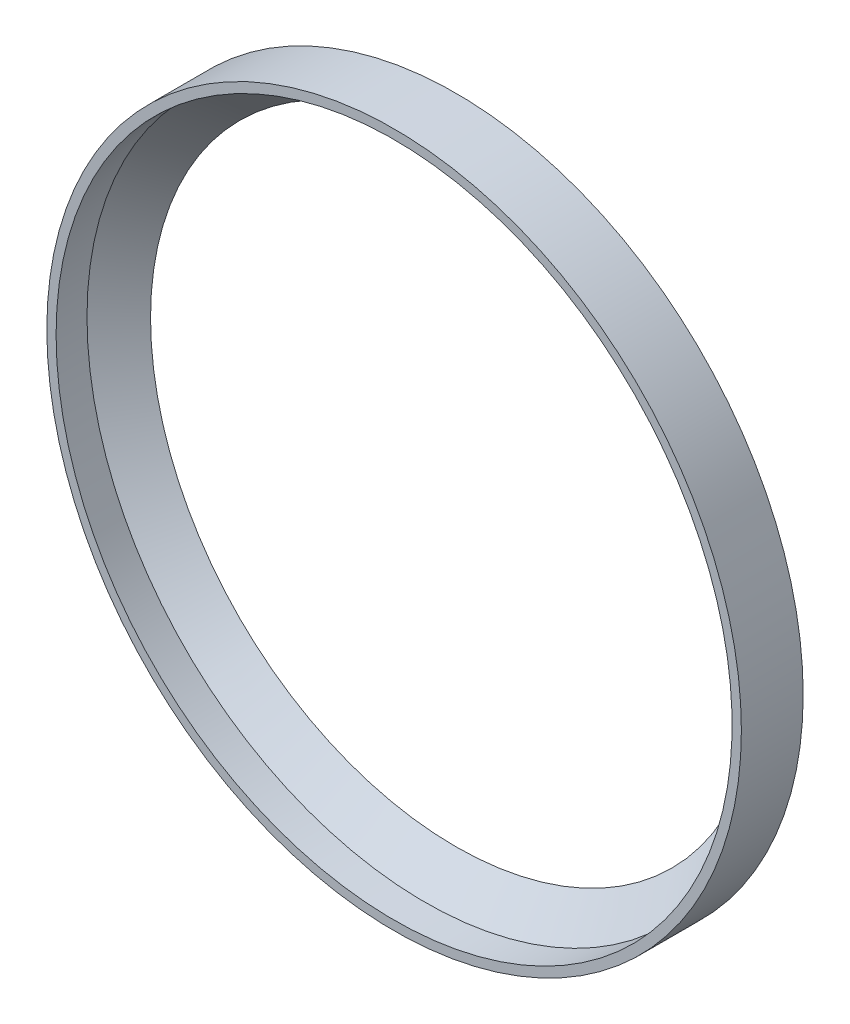
SolidWorks part; units mm, degrees
material "ABS"
ref_plane "Front Plane" through (0, 0, 0) normal (0, 0, 1) x (1, 0, 0)
ref_plane "Top Plane" through (0, 0, 0) normal (0, 1, 0) x (1, 0, 0)
ref_plane "Right Plane" through (0, 0, 0) normal (1, 0, 0) x (0, 0, -1)
sketch "Sketch1" plane through (0, 0, 0) normal (0, 1, 0) x (1, 0, 0)
  line L0 (0, 86.6876) -> (0, -87.5922) construction
  line L4 (138.9062, 0) -> (125.4885, 12.7)
  line L5 (142.7163, 0) -> (142.7163, 12.7)
  line L6 (142.7163, 12.7) -> (125.4885, 12.7)
  line L7 (142.7163, 0) -> (142.7163, -12.7)
  line L8 (142.7163, -12.7) -> (138.9063, -12.7)
  line L9 (138.9063, -12.7) -> (138.9062, 0)
  point P4 (0, 0)
  dimension "D1" = 138.9062
  dimension "D2" = 17.2277
  dimension "D3" = 12.7
  dimension "D4" = 133.426
  dimension "D5" = 3.81
  dimension "D6" = 12.7
  dimension "D7" = 73.9876
revolve "Revolve1" add sketch "Sketch1" angle 360 about L0
